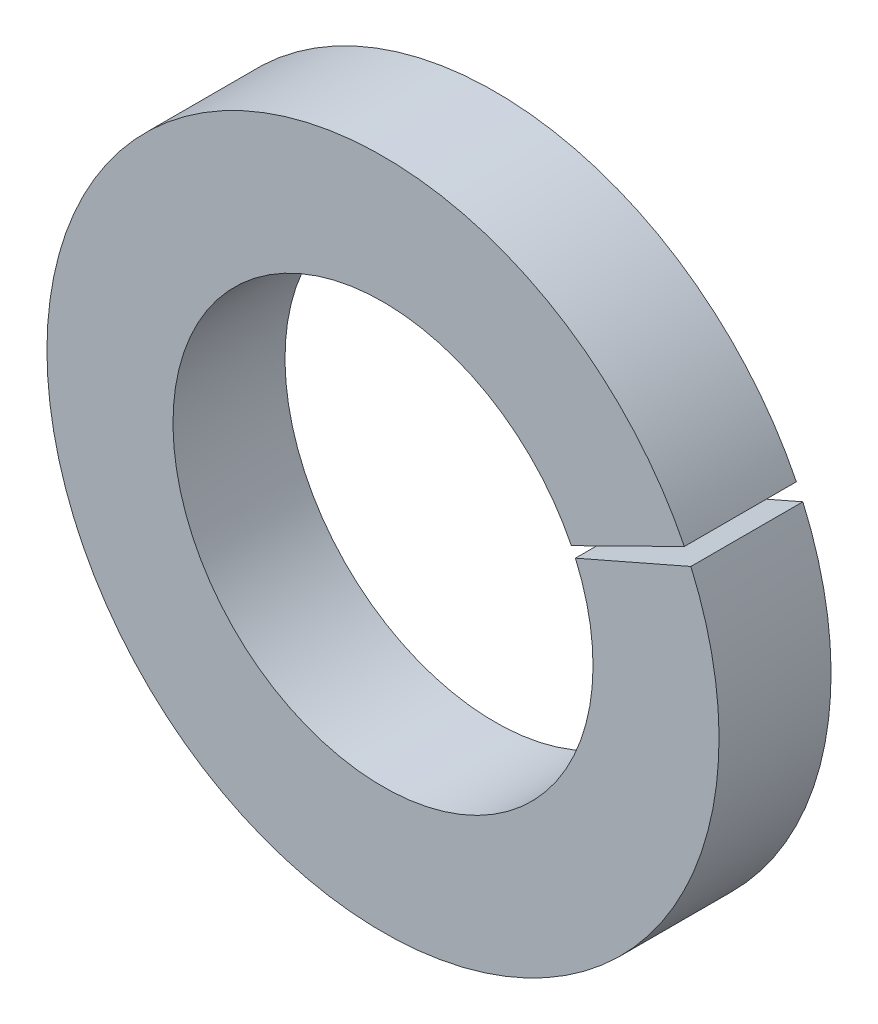
SolidWorks part; units mm, degrees
ref_plane "前视基准面" through (0, 0, 0) normal (0, 0, 1) x (1, 0, 0)
ref_plane "上视基准面" through (0, 0, 0) normal (0, 1, 0) x (1, 0, 0)
ref_plane "右视基准面" through (0, 0, 0) normal (1, 0, 0) x (0, 0, -1)
sketch "草图1" plane through (0, 0, 0) normal (0, 0, 1) x (1, 0, 0)
  circle A0 centre (0, 0) radius 4.8
  circle A1 centre (0, 0) radius 3
  dimension "D1" = 6
  dimension "D2" = 9.6
extrude "凸台-拉伸1" add sketch "草图1" along normal blind 1.6
sketch "草图2" plane through (0, 0, 1.6) normal (0, 0, 1) x (1, 0, 0)
  line L0 (0, 0) -> (4.8125, 2.3756)
  line L1 (4.8125, 2.3756) -> (4.8125, 2.1059)
  line L2 (4.8125, 2.1059) -> (0, 0)
extrude "切除-拉伸1" cut sketch "草图2" against normal blind 10
